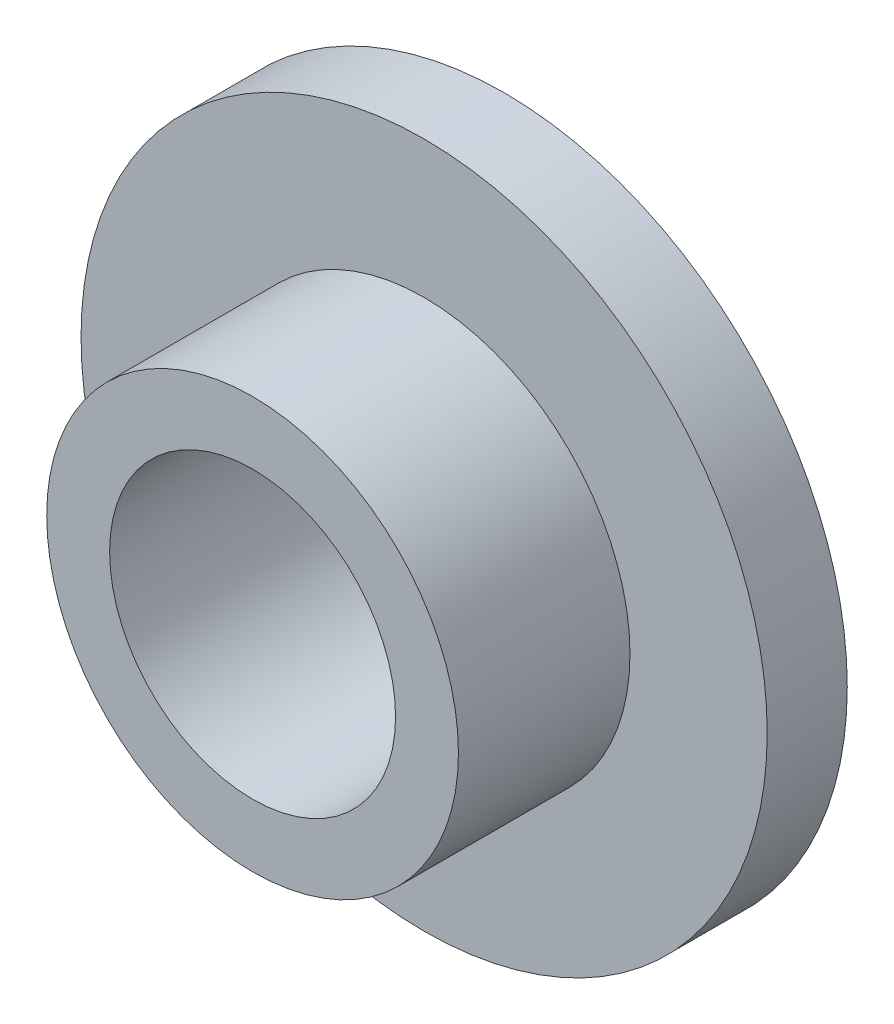
SolidWorks part; units mm, degrees
ref_plane "Спереди" through (0, 0, 0) normal (0, 0, 1) x (1, 0, 0)
ref_plane "Сверху" through (0, 0, 0) normal (0, 1, 0) x (1, 0, 0)
ref_plane "Справа" through (0, 0, 0) normal (1, 0, 0) x (0, 0, -1)
sketch "Эскиз1" plane through (0, 0, 0) normal (0, 0, 1) x (1, 0, 0)
  circle A0 centre (0, 0) radius 12.5
  circle A1 centre (0, 0) radius 30
extrude "Вытянуть1" add sketch "Эскиз1" along normal blind 7
sketch "Эскиз3" plane through (0, 0, 7) normal (0, 0, 1) x (1, 0, 0)
  circle A0 centre (0, 0) radius 12.5
  circle A1 centre (0, 0) radius 18
extrude "Вытянуть2" add sketch "Эскиз3" along normal blind 15
